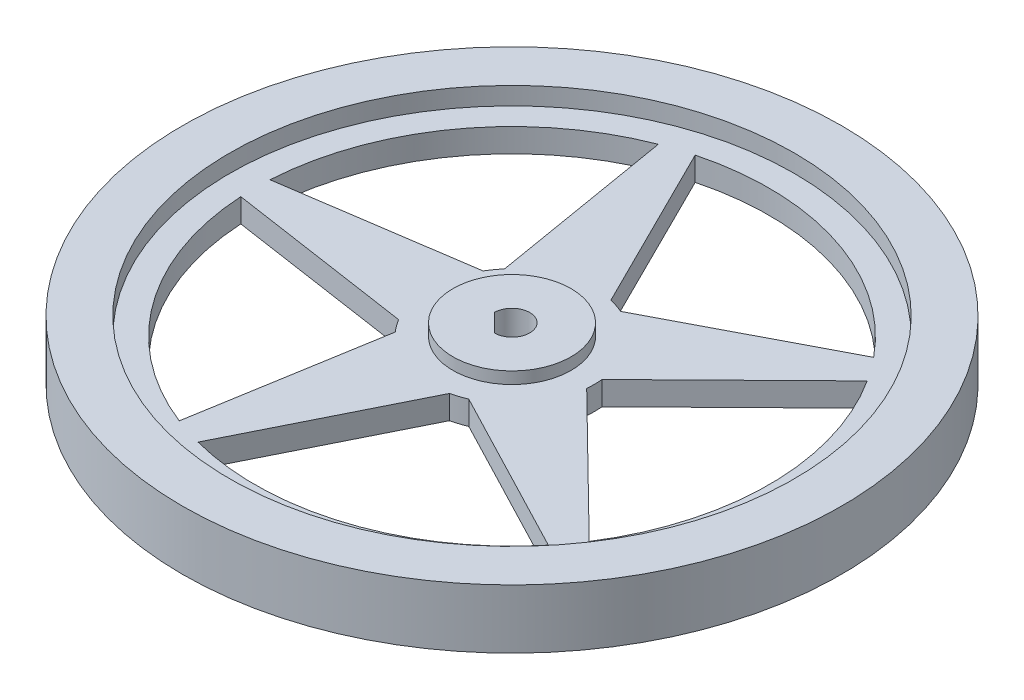
SolidWorks part; units mm, degrees
ref_plane "Front Plane" through (0, 0, 0) normal (0, 0, 1) x (1, 0, 0)
ref_plane "Top Plane" through (0, 0, 0) normal (0, 1, 0) x (1, 0, 0)
ref_plane "Right Plane" through (0, 0, 0) normal (1, 0, 0) x (0, 0, -1)
sketch "Sketch2" plane through (0, 0, 0) normal (1, 0, 0) x (0, 0, -1)
  line L1 (-55.78, -4) -> (-55.78, 4)
  line L2 (-55.78, 4) -> (-45.78, 4)
  line L3 (-45.78, 4) -> (-45.78, 2)
  line L4 (-45.78, 2) -> (-8, 2)
  line L5 (-8, 2) -> (-8, 5)
  line L6 (-8, 5) -> (0, 5)
  line L7 (0, 5) -> (0, -5)
  line L8 (-45.78, -4) -> (-45.78, -2)
  line L9 (-55.78, -4) -> (-45.78, -4)
  line L10 (-45.78, -2) -> (-8, -2)
  line L11 (-8, -2) -> (-8, -5)
  line L12 (-8, -5) -> (0, -5)
  dimension "D1" = 55.78
  dimension "D2" = 2
  dimension "D3" = 4
  dimension "D4" = 3
  dimension "D5" = 8
  dimension "D6" = 10
revolve "Revolve1" add sketch "Sketch2" angle 360 about L1
sketch "Sketch5" plane through (0, -4, 0) normal (0, -1, 0) x (1, 0, 0)
  line L0 (-3, 55.78) -> (0, 58.78)
  arc A0 (-3, 55.78) -> (0, 58.78) centre (0, 55.78) ccw
  dimension "D1" = 6
extrude "Cut-Extrude1" cut sketch "Sketch5" against normal blind 10
sketch "Sketch6" plane through (0, -2, 0) normal (0, -1, 0) x (-1, 0, 0)
  line L0 (43.5, -55.78) -> (14, -55.78) construction
  line L1 (43.4296, -58.2544) -> (12.0404, -62.9235)
  line L2 (43.4296, -53.3056) -> (12.0404, -48.6365)
  line L3 (11.0672, -97.8486) -> (-3.0732, -69.4385)
  line L4 (15.7737, -96.3193) -> (10.5145, -65.0236)
  line L5 (-36.5897, -79.3054) -> (-13.9397, -57.078)
  line L6 (-33.6809, -83.3091) -> (-5.542, -68.6364)
  line L7 (-33.6809, -28.2509) -> (-5.542, -42.9236)
  line L8 (-36.5897, -32.2546) -> (-13.9397, -54.482)
  line L9 (15.7737, -15.2407) -> (10.5145, -46.5364)
  line L10 (11.0672, -13.7114) -> (-3.0732, -42.1215)
  circle A0 centre (0, -55.78) radius 14
  circle A1 centre (0, -55.78) radius 43.5
  circle A2 centre (0, -55.78) radius 47.78 construction
  circle A3 centre (0, -55.78) radius 10 construction
  point P32 (0, -55.78)
  dimension "D1" = 28
  dimension "D2" = 87
  dimension "D3" = 12.0404
  dimension "D4" = 43.4296
  dimension "D5" = 5
extrude "Cut-Extrude3" cut sketch "Sketch6" against normal blind 10 contours L2 A1 L9 A0 | L4 A1 L1 A0 | L6 A1 L3 A0 | L8 A1 L5 A0 | L10 A1 L7 A0
